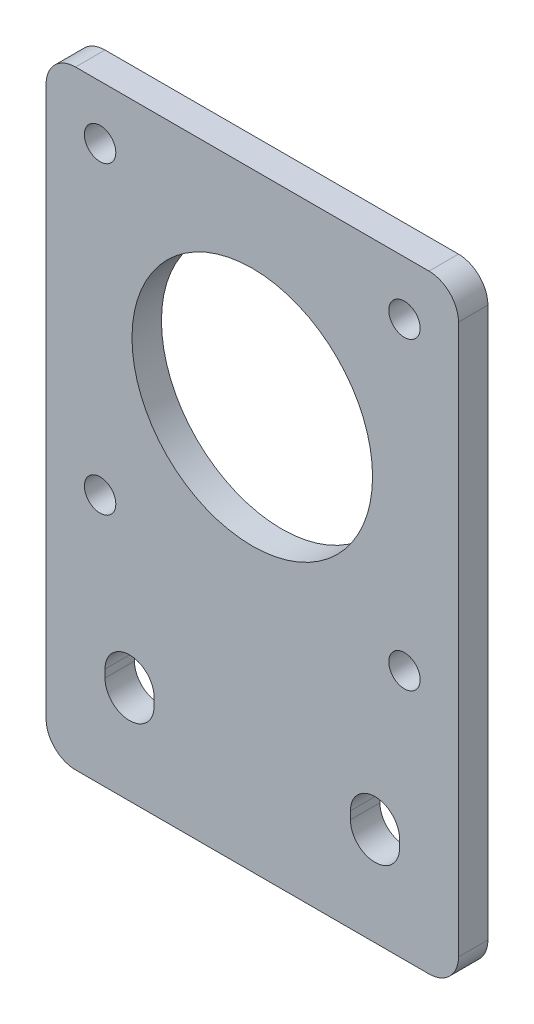
SolidWorks part; units mm, degrees
ref_plane "前视基准面" through (0, 0, 0) normal (0, 0, 1) x (1, 0, 0)
ref_plane "上视基准面" through (0, 0, 0) normal (0, 1, 0) x (1, 0, 0)
ref_plane "右视基准面" through (0, 0, 0) normal (1, 0, 0) x (0, 0, -1)
sketch "草图1" plane through (0, 0, 0) normal (0, 0, 1) x (1, 0, 0)
  line L0 (-1000, 0) -> (0, 0) construction
  line L1 (0, -1000) -> (0, 2.6548) construction
  line L2 (0, 35.9048) -> (0, 27.1548)
  line L3 (18, -26.0952) -> (-18, -26.0952)
  line L5 (18, 35.9048) -> (-18, 35.9048)
  line L6 (-21, -23.0952) -> (-21, 32.9048)
  line L7 (-12.5, -16.4952) -> (-12.5, -15.6952) construction
  line L8 (-15, -16.4952) -> (-15, -15.6952)
  line L9 (-10, -16.4952) -> (-10, -15.6952)
  line L10 (-15.5, 30.4048) -> (-15.5, -6.9604) construction
  line L11 (21, 0) -> (68.4076, 0) construction
  line L12 (0, 27.1548) -> (0, 56.242) construction
  line L13 (0, 2.6548) -> (0, -26.0952)
  line L14 (15.5, 30.4048) -> (15.5, -6.9604) construction
  line L15 (21, -23.0952) -> (21, 32.9048)
  line L16 (12.5, -16.4952) -> (12.5, -15.6952) construction
  line L17 (15, -16.4952) -> (15, -15.6952)
  line L18 (10, -16.4952) -> (10, -15.6952)
  line L19 (0, 14.9048) -> (42.8225, 14.9048) construction
  circle A0 centre (0, 14.9048) radius 12.25
  circle A2 centre (-15.5, 30.4048) radius 1.6
  circle A3 centre (-15.5, -0.5952) radius 1.6
  arc A4 (-18, 35.9048) -> (-21, 32.9048) centre (-18, 32.9048) ccw
  arc A6 (-21, -23.0952) -> (-18, -26.0952) centre (-18, -23.0952) ccw
  arc A7 (-15, -16.4952) -> (-10, -16.4952) centre (-12.5, -16.4952) ccw
  arc A8 (-10, -15.6952) -> (-15, -15.6952) centre (-12.5, -15.6952) ccw
  arc A9 (21, -23.0952) -> (18, -26.0952) centre (18, -23.0952) cw
  arc A10 (18, 35.9048) -> (21, 32.9048) centre (18, 32.9048) cw
  circle A11 centre (15.5, -0.5952) radius 1.6
  circle A12 centre (15.5, 30.4048) radius 1.6
  arc A13 (15, -16.4952) -> (10, -16.4952) centre (12.5, -16.4952) cw
  arc A14 (10, -15.6952) -> (15, -15.6952) centre (12.5, -15.6952) cw
  point P1 (0, 0)
  point P12 (-12.5, -16.0952)
  point P47 (12.5, -16.0952)
  dimension "D3" = 24.5
  dimension "D5" = 2.5
  dimension "D6" = 3.2
  dimension "D7" = 3.2
  dimension "D8" = 6
  dimension "D9" = 6
  dimension "D10" = 5.5
  dimension "D1" = 21
  dimension "D2" = 0.8
  dimension "D4" = 21
  dimension "D11" = 5.5
  dimension "D12" = 31
  dimension "D13" = 62
  dimension "D14" = 10
  dimension "D15" = 8.5
extrude "凸台-拉伸1" add sketch "草图1" along normal blind 3 contours L6 A6 L3 L13 A0 L2 L5 A4 A8 L9 A7 L8 A2 A3 | A10 L5 L2 A0 L13 L3 A9 L15 A11 A12 L18 A14 L17 A13
